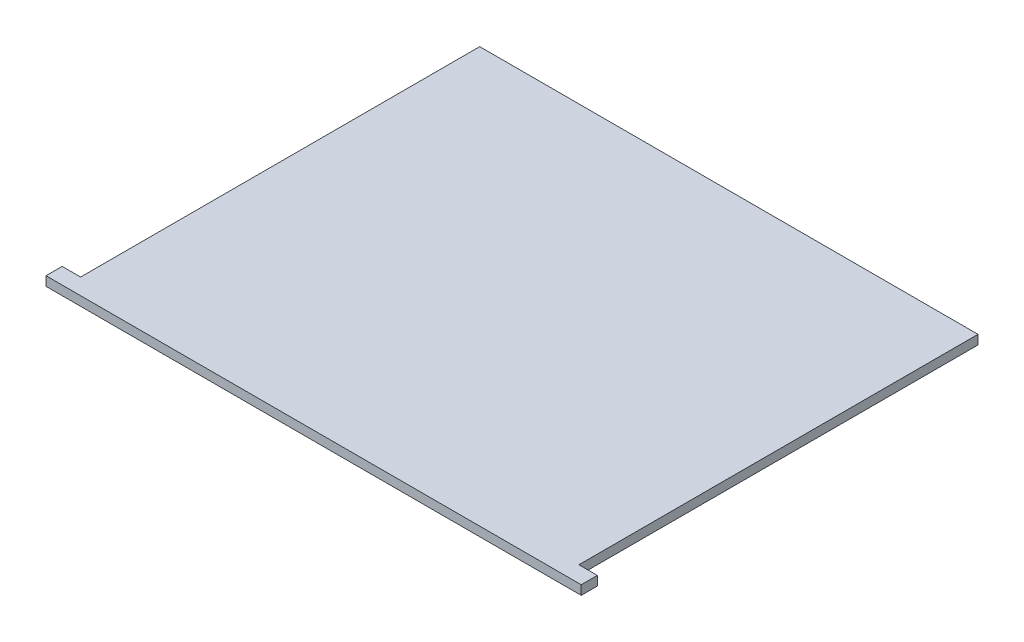
SolidWorks part; units mm, degrees
material "ABS"
ref_plane "Front Plane" through (0, 0, 0) normal (0, 0, 1) x (1, 0, 0)
ref_plane "Top Plane" through (0, 0, 0) normal (0, 1, 0) x (1, 0, 0)
ref_plane "Right Plane" through (0, 0, 0) normal (1, 0, 0) x (0, 0, -1)
sketch "Sketch1" plane through (0, 0, 0) normal (0, 1, 0) x (1, 0, 0)
  line L1 (-27, -22.5) -> (27, -22.5)
  line L3 (-27, 22.5) -> (27, 22.5)
  line L5 (-27, -22.5) -> (27, 22.5) construction
  line L6 (-27, 22.5) -> (27, -22.5) construction
  line L17 (-27, 22.5) -> (-27, -20.75)
  line L18 (-29, -20.75) -> (-29, -22.5)
  line L19 (-29, -22.5) -> (-27, -22.5)
  line L20 (-27, -20.75) -> (-29, -20.75)
  line L21 (27, 22.5) -> (27, -20.75)
  line L22 (27, -20.75) -> (29, -20.75)
  line L23 (29, -20.75) -> (29, -22.5)
  line L24 (29, -22.5) -> (27, -22.5)
  point P0 (0, 0)
  dimension "D1" = 1.75
  dimension "D2" = 2
  dimension "D3" = 54
  dimension "D4" = 45
  dimension "D5" = 2
  dimension "D6" = 1.75
extrude "Boss-Extrude1" add sketch "Sketch1" along normal blind 1
